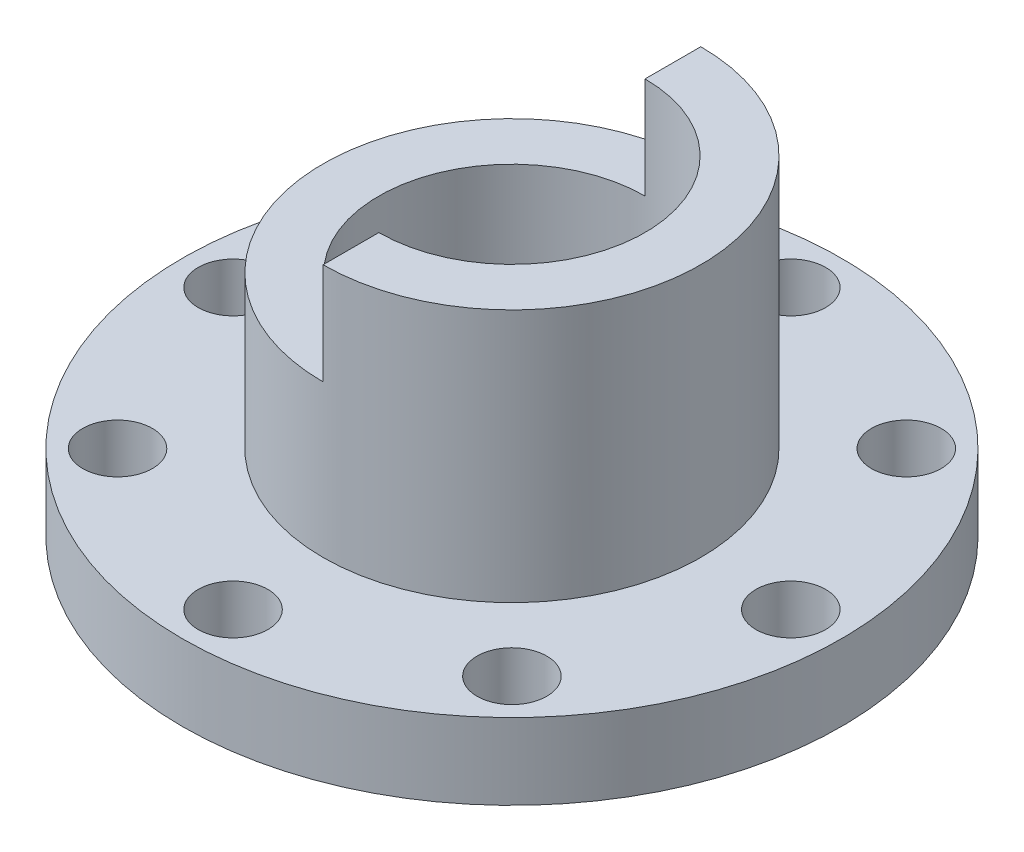
SolidWorks part; units mm, degrees
ref_plane "Front Plane" through (0, 0, 0) normal (0, 0, 1) x (1, 0, 0)
ref_plane "Top Plane" through (0, 0, 0) normal (0, 1, 0) x (1, 0, 0)
ref_plane "Right Plane" through (0, 0, 0) normal (1, 0, 0) x (0, 0, -1)
sketch "Sketch1" plane through (0, 0, 0) normal (0, 1, 0) x (1, 0, 0)
  circle A0 centre (0, 0) radius 11
  circle A1 centre (0, 11) radius 1.375
  circle A2 centre (7.7782, 7.7782) radius 1.375
  circle A3 centre (11, 0) radius 1.375
  circle A4 centre (7.7782, -7.7782) radius 1.375
  circle A5 centre (0, -11) radius 1.375
  circle A6 centre (-7.7782, -7.7782) radius 1.375
  circle A7 centre (-11, 0) radius 1.375
  circle A8 centre (-7.7782, 7.7782) radius 1.375
  circle A9 centre (0, 0) radius 13
  circle A10 centre (0, 0) radius 5
  point P21 (0, 0)
  dimension "D1" = 22
  dimension "D2" = 2.75
  dimension "D4" = 26
  dimension "D5" = 10
  dimension "D3" = 8
extrude "Boss-Extrude1" add sketch "Sketch1" along normal blind 3 contours A8 A0 A7 A6 A5 A4 A3 A2 A1 A10 | A9 A8 A0 A1 A2 A3 A4 A5 A6 A7
sketch "Sketch2" plane through (0, 3, 0) normal (0, 1, 0) x (1, 0, 0)
  circle A0 centre (0, 0) radius 5
  circle A1 centre (0, 0) radius 7.5
  dimension "D1" = 15
extrude "Boss-Extrude2" add sketch "Sketch2" along normal blind 10
sketch "Sketch3" plane through (0, 13, 0) normal (0, 1, 0) x (1, 0, 0)
  circle A0 centre (0, 0) radius 5.25
  dimension "D1" = 10.5
extrude "Cut-Extrude1" cut sketch "Sketch3" against normal blind 18
sketch "Sketch4" plane through (0, 13, 0) normal (0, 1, 0) x (1, 0, 0)
  line L0 (0, 7.5) -> (0, -7.5)
  circle A0 centre (0, 0) radius 7.5
  circle M1 centre (0, 0) radius 5.25
  circle M2 centre (0, 0) radius 7.5
extrude "Cut-Extrude2" cut sketch "Sketch4" against normal blind 4 contours L0 M2 M1
sketch "Sketch5" plane through (0, 13, 0) normal (0, 1, 0) x (1, 0, 0)
  circle A0 centre (0, 0) radius 7.5
  circle A1 centre (0, 0) radius 7.45
  dimension "D1" = 14.9
extrude "Cut-Extrude3" cut sketch "Sketch5" against normal blind 10
